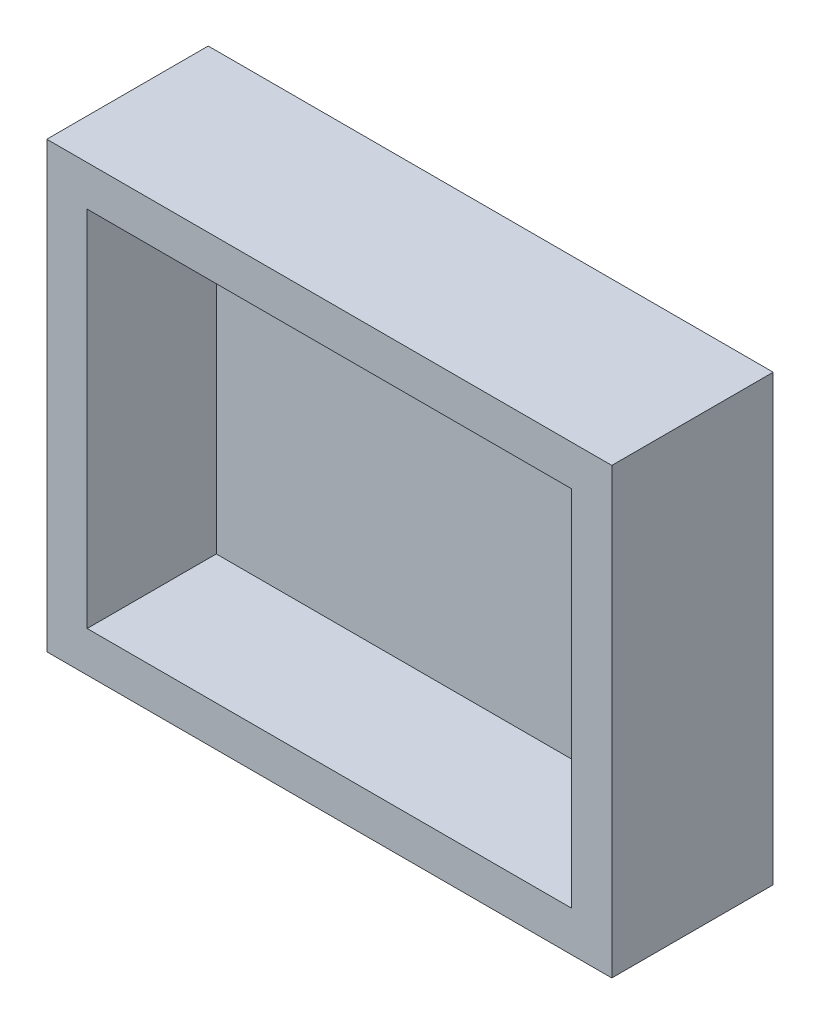
SolidWorks part; units mm, degrees
ref_plane "Front Plane" through (0, 0, 0) normal (0, 0, 1) x (1, 0, 0)
ref_plane "Top Plane" through (0, 0, 0) normal (0, 1, 0) x (1, 0, 0)
ref_plane "Right Plane" through (0, 0, 0) normal (1, 0, 0) x (0, 0, -1)
sketch "Sketch1" plane through (0, 0, 0) normal (0, 0, 1) x (1, 0, 0)
  line L1 (-42.2989, 11.128) -> (27.7011, 11.128)
  line L2 (-42.2989, 11.128) -> (-42.2989, -43.872)
  line L3 (-42.2989, -43.872) -> (27.7011, -43.872)
  line L4 (27.7011, 11.128) -> (27.7011, -43.872)
  line L5 (-37.2989, 6.128) -> (22.7011, 6.128)
  line L6 (-37.2989, 6.128) -> (-37.2989, -38.872)
  line L7 (-37.2989, -38.872) -> (22.7011, -38.872)
  line L8 (22.7011, 6.128) -> (22.7011, -38.872)
  dimension "D1" = 70
  dimension "D2" = 55
  dimension "D3" = 5
  dimension "D4" = 5
  dimension "D5" = 5
  dimension "D6" = 5
extrude "Boss-Extrude1" add sketch "Sketch1" along normal blind 20
sketch "Sketch2" plane through (0, 0, 0) normal (0, 0, 1) x (1, 0, 0)
  line L0 (-37.2989, -38.872) -> (22.7011, -38.872) construction
  line L1 (-37.2989, -38.872) -> (22.7011, -38.872)
  line L2 (-37.2989, -38.872) -> (-37.2989, 6.128)
  line L3 (-37.2989, 6.128) -> (22.7011, 6.128)
  line L4 (22.7011, -38.872) -> (22.7011, 6.128)
extrude "Boss-Extrude2" add sketch "Sketch2" along normal blind 4
